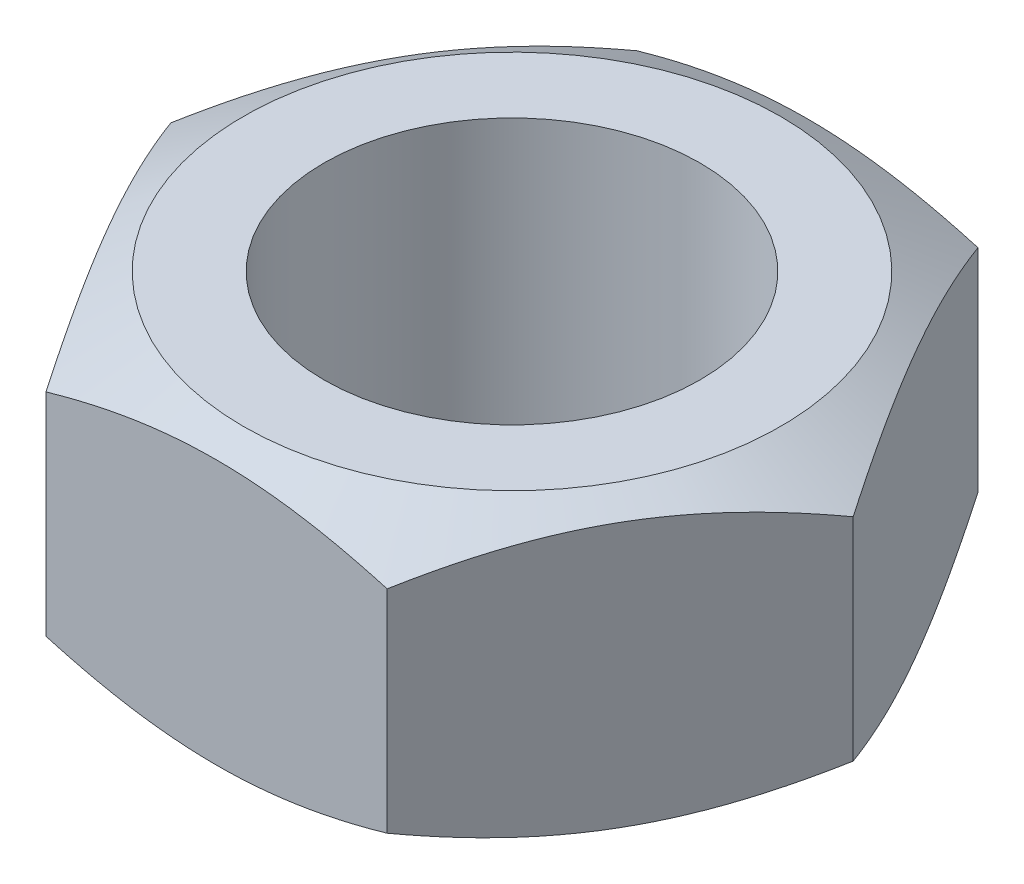
SolidWorks part; units mm, degrees
ref_plane "Alzado" through (0, 0, 0) normal (0, 0, 1) x (1, 0, 0)
ref_plane "Planta" through (0, 0, 0) normal (0, 1, 0) x (1, 0, 0)
ref_plane "Vista lateral" through (0, 0, 0) normal (1, 0, 0) x (0, 0, -1)
sketch "Croquis5" plane through (0, 0, 0) normal (0, 1, 0) x (1, 0, 0)
  line L0 (-12.7017, 0) -> (12.7017, 0) construction
  line L1 (12.7017, 0) -> (6.3509, 11)
  line L2 (6.3509, 11) -> (-6.3509, 11)
  line L3 (-6.3509, 11) -> (-12.7017, 0)
  line L4 (-12.7017, 0) -> (-6.3509, -11)
  line L5 (-6.3509, -11) -> (6.3509, -11)
  line L6 (6.3509, -11) -> (12.7017, 0)
  line L7 (0, 11) -> (0, -11) construction
  circle A0 centre (0, 0) radius 11 construction
  dimension "D1" = 22
extrude "Saliente-Extruir6" add sketch "Croquis5" along normal mid plane 11
sketch "Croquis6" plane through (0, 5.5, 0) normal (0, 1, 0) x (1, 0, 0)
  circle A0 centre (0, 0) radius 7
  dimension "D1" = 14
extrude "Cortar-Extruir1" cut sketch "Croquis6" against normal blind 11
sketch "Croquis10" plane through (0, 5.5, 0) normal (0, 1, 0) x (1, 0, 0)
  circle A0 centre (0, 0) radius 10
extrude "Cortar-Extruir2" cut sketch "Croquis10" against normal blind 10 draft 60 flip side to cut
sketch "Croquis11" plane through (0, -5.5, 0) normal (0, -1, 0) x (1, 0, 0)
  circle A0 centre (0, 0) radius 10
extrude "Cortar-Extruir3" cut sketch "Croquis11" against normal blind 10 draft 60 flip side to cut
sketch "Croquis20" plane through (0, 5.5, 0) normal (0, 1, 0) x (1, 0, 0)
  circle A0 centre (0, 0) radius 7 construction
  circle A1 centre (0, 0) radius 7
